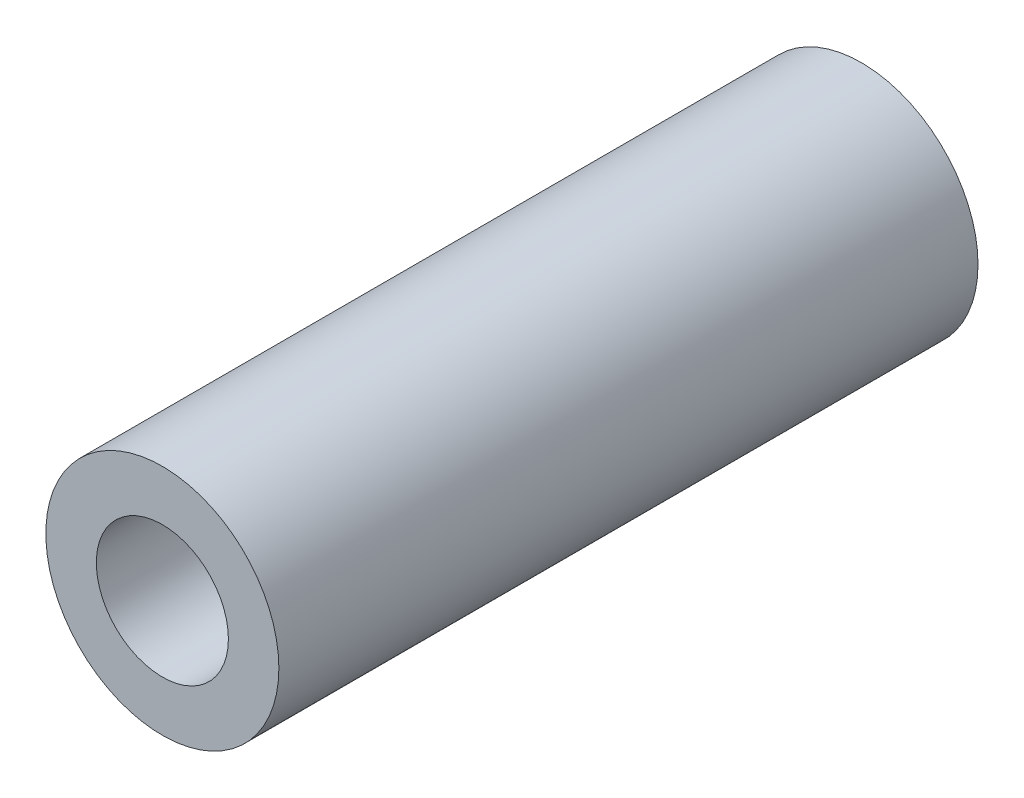
SolidWorks part; units mm, degrees
other "Controller Shelf Post 1"
ref_plane "Front Plane" through (0, 0, 0) normal (0, 0, 1) x (1, 0, 0)
ref_plane "Top Plane" through (0, 0, 0) normal (0, 1, 0) x (1, 0, 0)
ref_plane "Right Plane" through (0, 0, 0) normal (1, 0, 0) x (0, 0, -1)
sketch3d "Main Profile Sketch datum points"
  point P0 (0, 0, 66.5)
  point P1 (10, 0, 66.5)
  point P2 (0, 10, 66.5)
ref_plane "Main Profile Sketch plane" through (0, 0, 66.5) normal (0, 0, 1) x (1, 0, 0)
sketch "Main Profile Sketch" plane through (0, 0, 66.5) normal (0, 0, 1) x (1, 0, 0)
  circle A0 centre (-155, -45) radius 3
  circle A1 centre (-155, -45) radius 1.7
extrude "Main Extrusion" add sketch "Main Profile Sketch" against normal blind 18 separate body
